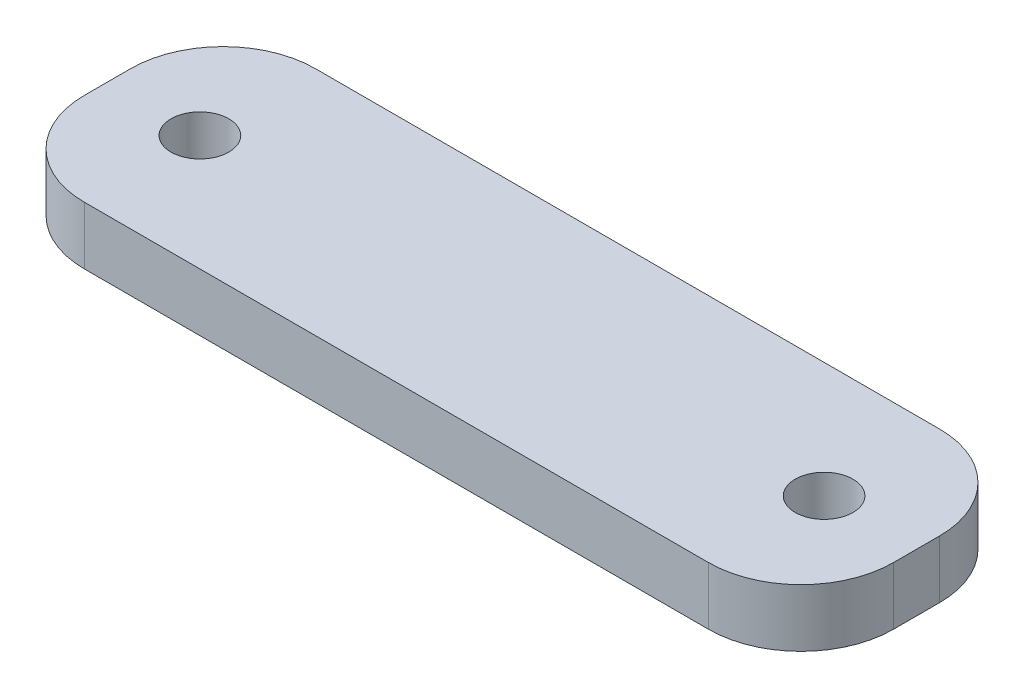
SolidWorks part; units mm, degrees
ref_plane "Front Plane" through (0, 0, 0) normal (0, 0, 1) x (1, 0, 0)
ref_plane "Top Plane" through (0, 0, 0) normal (0, 1, 0) x (1, 0, 0)
ref_plane "Right Plane" through (0, 0, 0) normal (1, 0, 0) x (0, 0, -1)
sketch "Sketch1" plane through (0, 0, 0) normal (0, 1, 0) x (1, 0, 0)
  line L0 (8, 0) -> (8, -20) construction
  line L1 (8, 0) -> (62, 0)
  line L2 (0, -8) -> (0, -12)
  line L3 (8, -20) -> (62, -20)
  line L4 (70, -8) -> (70, -12)
  line L5 (35, 0) -> (35, -20) construction
  arc A0 (0, -12) -> (8, -20) centre (8, -12) ccw
  arc A1 (8, 0) -> (0, -8) centre (8, -8) ccw
  circle A2 centre (8, -10) radius 2.5
  arc A3 (62, -20) -> (70, -12) centre (62, -12) ccw
  arc A4 (62, 0) -> (70, -8) centre (62, -8) cw
  circle A5 centre (62, -10) radius 2.5
  point P7 (0, -20)
  point P10 (0, 0)
  point P17 (70, 0)
  dimension "D3" = 8
  dimension "D4" = 5
  dimension "D5" = 8
  dimension "D1" = 70
  dimension "D2" = 20
extrude "Boss-Extrude1" add sketch "Sketch1" along normal blind 5
